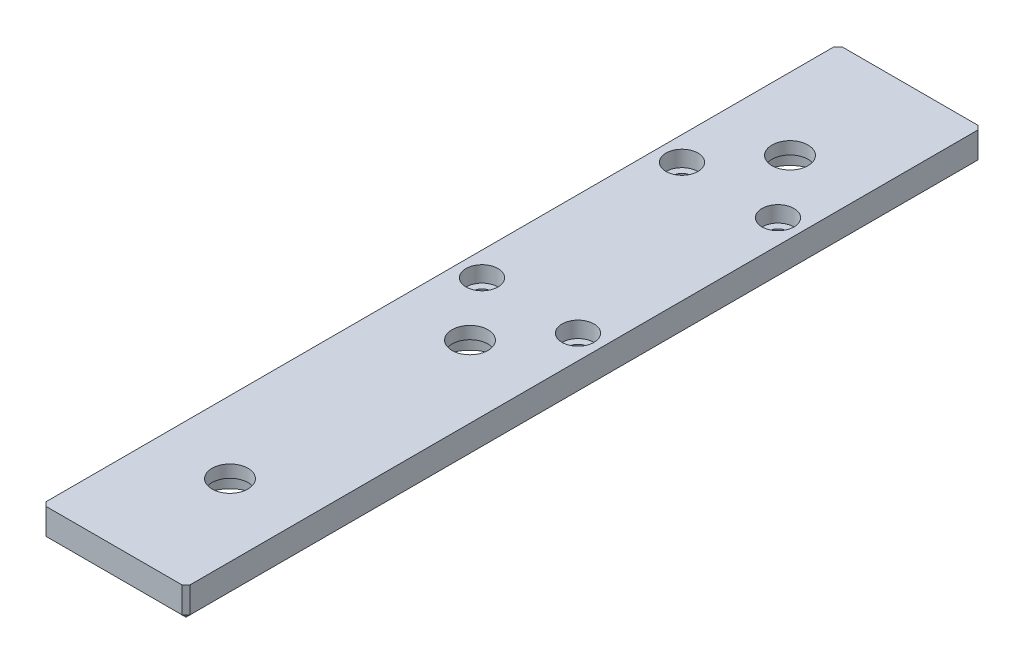
SolidWorks part; units mm, degrees
ref_plane "Front Plane" through (0, 0, 0) normal (0, 0, 1) x (1, 0, 0)
ref_plane "Top Plane" through (0, 0, 0) normal (0, 1, 0) x (1, 0, 0)
ref_plane "Right Plane" through (0, 0, 0) normal (1, 0, 0) x (0, 0, -1)
sketch "Sketch1" plane through (0, 0, 0) normal (0, 1, 0) x (1, 0, 0)
  line L1 (-18, 99.5) -> (18, 99.5)
  line L2 (-18, 99.5) -> (-18, -99.5)
  line L3 (-18, -99.5) -> (18, -99.5)
  line L4 (18, 99.5) -> (18, -99.5)
  line L5 (-18, 99.5) -> (18, -99.5) construction
  line L6 (-18, -99.5) -> (18, 99.5) construction
  point P0 (0, 0)
  dimension "D1" = 199
  dimension "D2" = 36
extrude "Boss-Extrude1" add sketch "Sketch1" along normal blind 7.5
hole_wizard "CBORE for M4 SHCS1" positions "Sketch2" profile "Sketch3" counterbore size "M4" standard "ANSI Metric" end condition through all
sketch "Sketch2" plane through (0, 7.5, 0) normal (0, 1, 0) x (1, 0, 0)
  line L0 (-12, 54.5) -> (12, 4.5) construction
  line L2 (18, 99.5) -> (-18, 99.5) construction
  point P0 (-12, 54.5)
  point P2 (12, 54.5)
  point P4 (12, 4.5)
  point P6 (-12, 4.5)
  point P22 (0, 29.5)
  dimension "D1" = 50
  dimension "D2" = 24
  dimension "D3" = 70
sketch "Sketch3" plane through (-12, 7.5, -54.5) normal (1, 0, 0) x (0, 0, 1)
  line L0 (0, 0) -> (0, 7.5)
  line L1 (0, 7.5) -> (2.25, 7.5)
  line L3 (2.25, 7.5) -> (2.25, 4)
  line L4 (2.25, 4) -> (4, 4)
  line L5 (4, 4) -> (4, 0)
  line L7 (4, 0) -> (0, 0)
  line L11 (0, -6.35) -> (0, 107.95) construction
  dimension "Thru Hole Dia." = 4.5
  dimension "Thru Hole Depth" = 7.5
  dimension "C'Bore Dia." = 8
  dimension "C'Bore Depth" = 4
chamfer "Chamfer1" distance 1 angle 45 12 edges at (-18, 7.5, 0) (-18, 3.75, -99.5) (0, 7.5, -99.5) (18, 3.75, -99.5) (18, 7.5, 0) (-18, 3.75, 99.5) (0, 7.5, 99.5) (18, 3.75, 99.5) (0, 0, -99.5) (-18, 0, 0) (0, 0, 99.5) (18, 0, 0)
hole_wizard "CBORE for M8 SBHCS1" positions "Sketch4" profile "Sketch5" counterbore size "M8" standard "ANSI Metric" end condition through all
sketch "Sketch4" plane through (0, 0, 0) normal (0, -1, 0) x (-1, 0, 0)
  line L0 (0, 69.5) -> (0, -10.5) construction
  line L2 (-17, 99.5) -> (17, 99.5) construction
  point P0 (0, 69.5)
  point P2 (0, -10.5)
  point P4 (0, -70.5)
  point P10 (0, 29.5)
  dimension "D1" = 80
  dimension "D2" = 60
  dimension "D3" = 70
sketch "Sketch5" plane through (0, 0, -69.5) normal (1, 0, 0) x (0, 0, -1)
  line L0 (0, 0) -> (0, 7.5)
  line L1 (0, 7.5) -> (4.5, 7.5)
  line L3 (4.5, 7.5) -> (4.5, 4.4)
  line L4 (4.5, 4.4) -> (7.5, 4.4)
  line L5 (7.5, 4.4) -> (7.5, 0)
  line L7 (7.5, 0) -> (0, 0)
  line L11 (0, -6.35) -> (0, 107.95) construction
  dimension "Thru Hole Dia." = 9
  dimension "Thru Hole Depth" = 7.5
  dimension "C'Bore Dia." = 15
  dimension "C'Bore Depth" = 4.4
